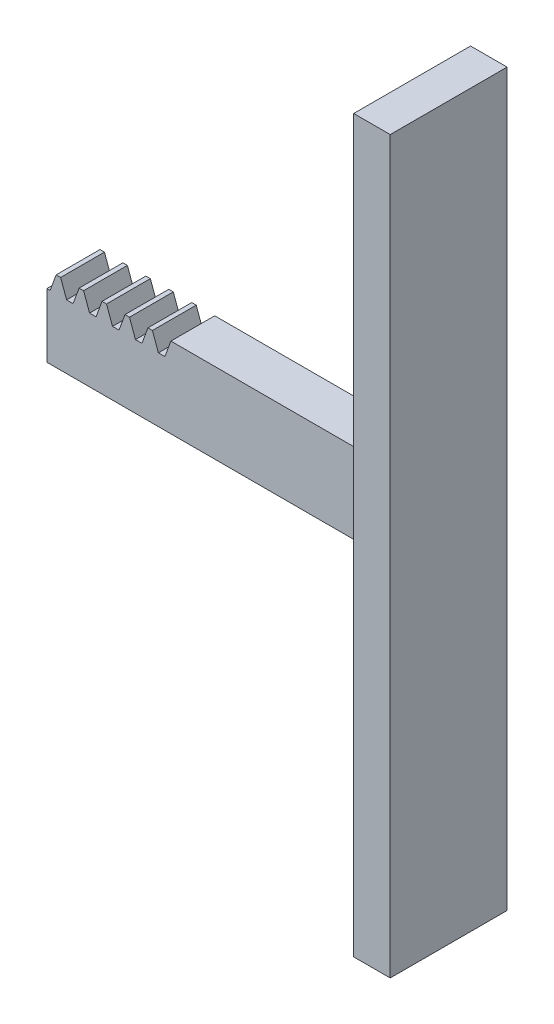
SolidWorks part; units mm, degrees
extrude "Blank" add sketch "BlankSke" against normal blind 6
sketch "BlankSke" plane through (0, 0, 0) normal (0, 0, 1) x (1, 0, 0)
  line L1 (0, 0) -> (17, 0)
  line L2 (0, 0) -> (0, 11)
  line L3 (0, 11) -> (17, 11)
  line L4 (17, 0) -> (17, 11)
  dimension "Length" = 17
  dimension "Blank_height" = 11
ref_plane "Plane1" through (0, 0, 0) normal (0, 0, 1) x (1, 0, 0)
ref_plane "Plane2" through (0, 0, 0) normal (0, 1, 0) x (1, 0, 0)
ref_plane "Plane3" through (0, 0, 0) normal (1, 0, 0) x (0, 0, -1)
sketch "HoldingSke" plane through (0, 0, 0) normal (0, 1, 0) x (1, 0, 0)
  line L0 (0, 0) -> (0.1392, 0.9903)
  line L1 (-15, 0) -> (100, 0) construction
  line L2 (0, 0) -> (-2.1039, 2.3779)
  line L3 (0, 0) -> (-11.863, 4.5341)
  line L4 (0, 0) -> (8.5716, 1.0524)
  line L5 (0, 0) -> (-23.7986, -8.8762)
  line L6 (0, 0) -> (-10.5278, -7.1032)
  line L9 (-71.009, 38.7566) -> (-55.0342, 44.571)
  line L10 (-76.2, 3.3779) -> (-66.2, 3.3779)
  line L11 (0, 0) -> (-6, 0)
  line L12 (-76.2, 101.6) -> (-76.162, 101.6)
  line L13 (24.9733, 27.94) -> (52.9518, 28.4284)
  line L14 (24.9733, 27.94) -> (24.9743, 27.94)
  line L15 (24.9733, 27.94) -> (100.4006, 29.5858)
  circle A0 centre (0, 0) radius 19.05
  circle A1 centre (0, 0) radius 5
  circle A2 centre (0, 0) radius 12.7
  dimension "MPH" = 10
  dimension "Diameter" = 38.1
  dimension "Num_teeth" = 7
  dimension "Pitch" = 1
  dimension "Show_teeth" = 998
  dimension "Thickness" = 12.7
  dimension "Ap" = 20
  dimension "Pitch_height" = 10
  dimension "Width" = 6
  dimension "Backlash" = 0.038
  dimension "Addendum_fac" = 1
  dimension "Dedendum_fac" = 1.25
  dimension "Clearance_fac" = 0.25
  dimension "Dedendum_add" = 0.001
  dimension "Length" = 17
  dimension "Module" = 1
sketch "TooCutSkeIll" plane through (0, 0, 0) normal (0, 0, 1) x (1, 0, 0)
  line L0 (-1.2538, 10.9737) -> (-0.5045, 8.9152)
  line L1 (-0.2687, 8.75) -> (0.2687, 8.75)
  line L2 (0.5045, 8.9152) -> (1.2538, 10.9737)
  line L3 (17, 11) -> (0, 11) construction
  line L4 (0, 0) -> (0, 64.897) construction
  line L5 (-13.208, 10) -> (12.954, 10) construction
  line L6 (0, 0) -> (17, 0) construction
  line L7 (0.8994, 10) -> (0.8994, 48.7463) construction
  line L8 (-0.8994, 10) -> (-0.8994, 48.7463) construction
  line L9 (1.2914, 11) -> (1.2914, 11.0254)
  line L10 (-1.2914, 11) -> (-1.2914, 11.0254)
  line L11 (-1.2914, 11.0254) -> (1.2914, 11.0254)
  arc A0 (0.2687, 8.75) -> (0.5045, 8.9152) centre (0.2687, 9.001) ccw
  arc A1 (-0.5045, 8.9152) -> (-0.2687, 8.75) centre (-0.2687, 9.001) ccw
  arc A2 (1.2914, 11) -> (1.2538, 10.9737) centre (1.2914, 10.96) ccw
  arc A3 (-1.2538, 10.9737) -> (-1.2914, 11) centre (-1.2914, 10.96) ccw
  dimension "Pitch_height" = 10
  dimension "Addendum_plus" = 1.0254
  dimension "Pressure_angle" = 20
  dimension "Gap_width" = 1.7988
  dimension "Dedendum" = 1.25
extrude "ToothCutIll" [suppressed] cut sketch "TooCutSkeIll" against normal through all
sketch "TooCutSkeSim" plane through (0, 0, 0) normal (0, 0, 1) x (1, 0, 0)
  line L0 (0.4444, 8.75) -> (-0.4444, 8.75)
  line L1 (1.2726, 11.0254) -> (0.4444, 8.75)
  line L2 (0, 17.4625) -> (0, 53.467) construction
  line L3 (1.2726, 11.0254) -> (-1.2726, 11.0254)
  line L6 (-1.2726, 11.0254) -> (-0.4444, 8.75)
  line L9 (-0.8994, 10) -> (0.8994, 10) construction
  line L10 (0, 0) -> (17, 0) construction
  line L11 (0.8994, 10) -> (0.8994, 53.467) construction
  line L12 (-0.8994, 10) -> (-0.8994, 53.467) construction
  dimension "Pitch_height" = 10
  dimension "Addendum_plus" = 1.0254
  dimension "Pressure_angle" = 20
  dimension "Gap_width" = 1.7988
  dimension "Dedendum" = 1.25
extrude "ToothCutSim" cut sketch "TooCutSkeSim" against normal through all
pattern_linear "TeethCuts" count 6 spacing 3.1416 along (1, 0, 0) of "ToothCutIll", "ToothCutSim"
sketch "草图1" plane through (17, 0, 0) normal (1, 0, 0) x (0, 0, -1)
  line L1 (0, 11) -> (6, 11)
  line L2 (0, 11) -> (0, 0)
  line L3 (0, 0) -> (6, 0)
  line L4 (6, 11) -> (6, 0)
extrude "凸台-拉伸1" add sketch "草图1" along normal blind 30
sketch "草图2" plane through (47, 0, 0) normal (1, 0, 0) x (0, 0, -1)
  line L0 (3, 11) -> (3, 0) construction
  line L1 (6, 11) -> (0, 11) construction
  line L2 (0, 0) -> (6, 0) construction
  line L3 (3, 5.5) -> (3, -44.5) construction
  line L4 (3, 5.5) -> (3, 55.5) construction
  line L5 (-5, 55.5) -> (11, 55.5) construction
  line L7 (-5, 55.5) -> (11, 55.5)
  line L8 (-5, 55.5) -> (-5, -44.5)
  line L9 (-5, -44.5) -> (11, -44.5)
  line L10 (11, 55.5) -> (11, -44.5)
  point P14 (3, 55.5)
  dimension "D2" = 50
  dimension "D1" = 50
  dimension "D3" = 8
  dimension "D4" = 100
  dimension "D5" = 16
extrude "凸台-拉伸2" add sketch "草图2" along normal blind 5
equation "' \"Module@HoldingSke\" = 6.35"
equation "' \"Num_teeth@HoldingSke\" = 12"
equation "' \"Ap@HoldingSke\" =  20"
equation "' \"Ap@HoldingSke\" = 20"
equation "' \"Width@HoldingSke\" = 0.25 * 25.4"
equation "' \"Show_teeth@HoldingSke\" = 500"
equation "' \"Backlash@HoldingSke\" = 0.009 * 25.4"
equation "' \"Addendum_fac@HoldingSke\" = 1.0"
equation "' \"Dedendum_fac@HoldingSke\" = 1.25"
equation "' \"Dedendum_add@HoldingSke\" = 0.00005 * 25.4"
equation "' \"Clearance_fac@HoldingSke\" = 0.25"
equation "' \"Pitch_height@HoldingSke\" = 1 * 25.4"
equation "' \"Length@HoldingSke\" = 4.71 * 25.4"
equation "\"Pitch@HoldingSke\" = 1 / \"Module@HoldingSke\""
equation "\"MPH@HoldingSke\" = \"Dedendum_fac@HoldingSke\" / \"Pitch@HoldingSke\" + 2 * \"Dedendum_add@HoldingSke\" + 0.002 * 25.4"
equation "\"MPH@HoldingSke\" = ((sgn( \"MPH@HoldingSke\" - \"Pitch_height@HoldingSke\")+1)*( \"MPH@HoldingSke\" - \"Pitch_height@HoldingSke\"))/2 + \"Pitch_height@HoldingSke\""
equation "\"Blank_height@BlankSke\" = \"Pitch_height@HoldingSke\" + \"Addendum_fac@HoldingSke\"  / \"Pitch@HoldingSke\" "
equation "\"Length@BlankSke\" =  \"Length@HoldingSke\""
equation "\"Face_width@Blank\" = \"Width@HoldingSke\""
equation "\"Pressure_angle@TooCutSkeIll\" = \"Ap@HoldingSke\""
equation "\"Addendum_plus@TooCutSkeIll\" =  \"Addendum_fac@HoldingSke\"  / \"Pitch@HoldingSke\" + 0.001 *25.4"
equation "\"Dedendum@TooCutSkeIll\" = \"Dedendum_fac@HoldingSke\"  / \"Pitch@HoldingSke\""
equation "\"Pitch_height@TooCutSkeIll\" =  \"MPH@HoldingSke\""
equation "\"Gap_width@TooCutSkeIll\" = 3.14159265 / 2 / \"Pitch@HoldingSke\" + 6 * \"Backlash@HoldingSke\""
equation "\"Pressure_angle@TooCutSkeSim\" = \"Ap@HoldingSke\""
equation "\"Addendum_plus@TooCutSkeSim\" =  \"Addendum_fac@HoldingSke\"  / \"Pitch@HoldingSke\" + 0.001 * 25.4"
equation "\"Dedendum@TooCutSkeSim\" = \"Dedendum_fac@HoldingSke\"  / \"Pitch@HoldingSke\""
equation "\"Pitch_height@TooCutSkeSim\" =  \"MPH@HoldingSke\""
equation "\"Gap_width@TooCutSkeSim\" = 3.14159265 / 2 / \"Pitch@HoldingSke\" + 6 * \"Backlash@HoldingSke\""
equation "\"Root_fillet@TooCutSkeIll\" = \"Clearance_fac@HoldingSke\" / \"Pitch@HoldingSke\" + \"Dedendum_add@HoldingSke\""
equation "\"Break_rad@TooCutSkeIll\" = 0.02 / \"Pitch@HoldingSke\" * 2"
equation "\"Linear_pitch@TeethCuts\" = 3.14159265 / \"Pitch@HoldingSke\""
equation "\"Num_teeth@HoldingSke\" = int( ( \"Length@HoldingSke\" + 0 ) / (3.14159265 / \"Pitch@HoldingSke\")) + 0.9999  + 1"
equation " \"Num_teeth@TeethCuts\" = int( \"Show_teeth@HoldingSke\" ) + 1"
equation " \"Num_teeth@TeethCuts\" = ((sgn( \"Num_teeth@TeethCuts\" - \"Num_teeth@HoldingSke\" )-1)*( \"Num_teeth@TeethCuts\" - \"Num_teeth@HoldingSke\" ))/-2+ \"Num_teeth@HoldingSke\""
equation " \"Num_teeth@TeethCuts\" = ((sgn( \"Num_teeth@TeethCuts\" - 2.0)+1)*( \"Num_teeth@TeethCuts\" - 2.0))/2 +2.0"
